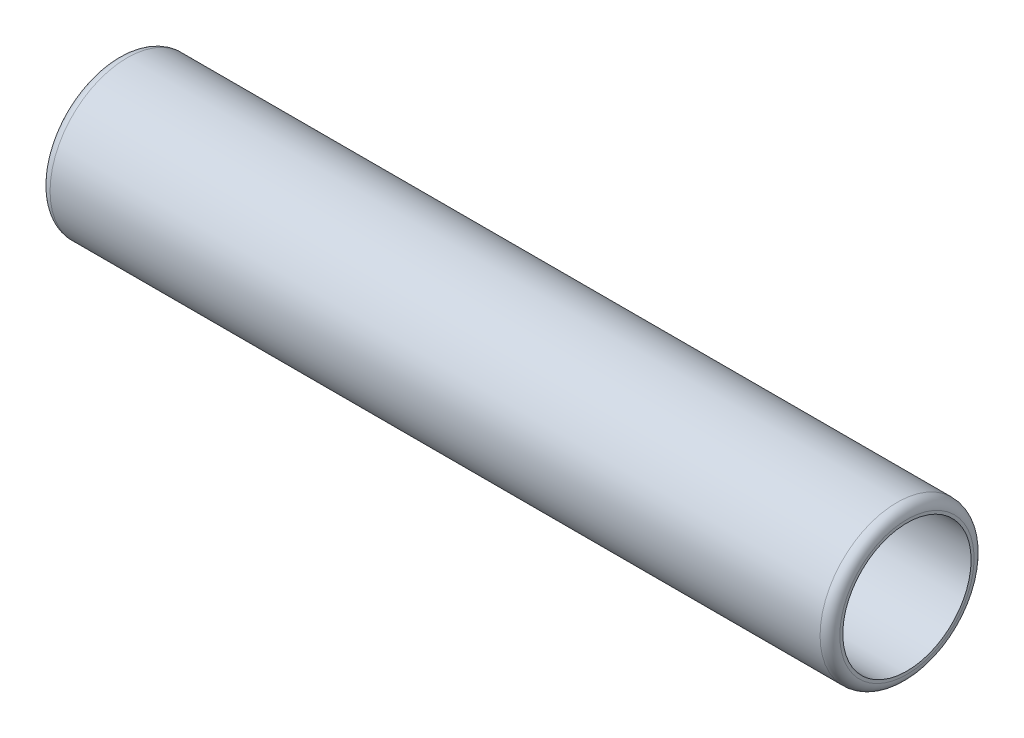
SolidWorks part; units mm, degrees
material "AISI 1045 Aço, trefilado"
ref_plane "Plano frontal" through (0, 0, 0) normal (0, 0, 1) x (1, 0, 0)
ref_plane "Plano superior" through (0, 0, 0) normal (0, 1, 0) x (1, 0, 0)
ref_plane "Plano direito" through (0, 0, 0) normal (1, 0, 0) x (0, 0, -1)
sketch "Esboço1" plane through (0, 0, 0) normal (0, 0, 1) x (1, 0, 0)
  line L0 (-40, 0) -> (40, 0)
  line L1 (-40, 0) -> (-40, 7.8)
  line L2 (-40, 7.8) -> (40, 7.8)
  line L3 (40, 7.8) -> (40, 0)
  point P4 (0, 0)
  dimension "D1" = 80
  dimension "D2" = 7.8
revolve "Revolução1" add sketch "Esboço1" angle 360 about L0
sketch "Esboço2" plane through (40, 0, 0) normal (1, 0, 0) x (0, 0, -1)
  circle A0 centre (0, 0) radius 6.5
  dimension "D1" = 13
extrude "Corte-extrusão1" cut sketch "Esboço2" against normal blind 25
sketch "Esboço3" plane through (15, 0, 0) normal (1, 0, 0) x (0, 0, -1)
  circle A0 centre (0, 0) radius 4.25
  dimension "D1" = 8.5
extrude "Corte-extrusão2" cut sketch "Esboço3" against normal through all and the other way through all
fillet "Filete1" radius 1 2 edges at (40, 0, 7.8) (-40, 0, 7.8)
